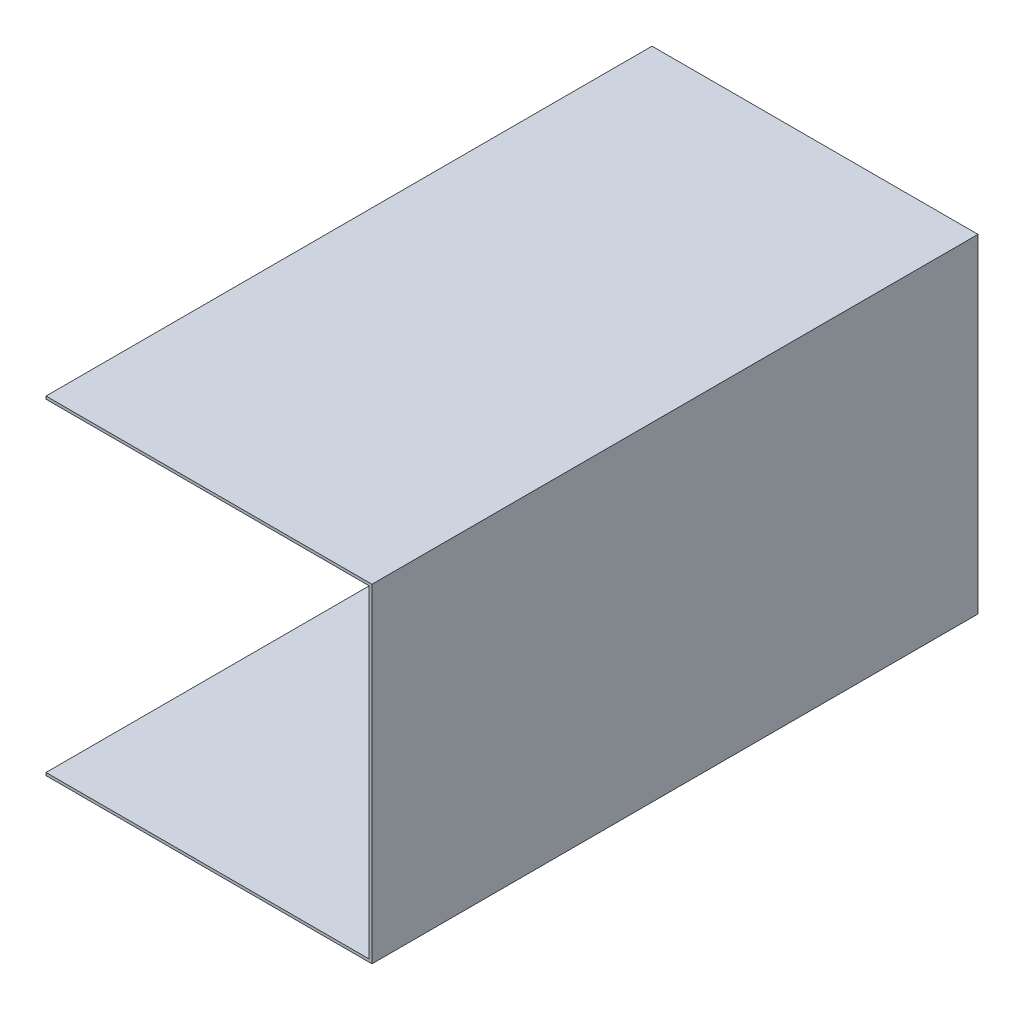
SolidWorks part; units mm, degrees
material "Beech"
ref_plane "Front Plane" through (0, 0, 0) normal (0, 0, 1) x (1, 0, 0)
ref_plane "Top Plane" through (0, 0, 0) normal (0, 1, 0) x (1, 0, 0)
ref_plane "Right Plane" through (0, 0, 0) normal (1, 0, 0) x (0, 0, -1)
sketch "Sketch1" plane through (0, 0, 0) normal (0, 0, 1) x (1, 0, 0)
  line L0 (-320, -320) -> (-320, -325.5)
  line L1 (-320, -320) -> (320, -320)
  line L2 (-320, -320) -> (-320, 320)
  line L3 (-320, 320) -> (320, 320)
  line L4 (320, -320) -> (320, 320)
  line L5 (-320, -320) -> (320, 320) construction
  line L6 (-320, 320) -> (320, -320) construction
  line L7 (-320, -325.5) -> (325.5, -325.5)
  line L9 (-320, 325.5) -> (325.5, 325.5)
  line L10 (325.5, -325.5) -> (325.5, 325.5)
  line L11 (-320, -320) -> (325.5, 325.5) construction
  line L12 (-320, 320) -> (325.5, -325.5) construction
  line L13 (-320, 320) -> (-320, 325.5)
  point P0 (0, 0)
  point P6 (0, 0)
  dimension "D1" = 640
  dimension "D2" = 5.5
extrude "Boss-Extrude1" add sketch "Sketch1" along normal blind 1200 contours L13 L3 L4 L1 L0 L7 L10 L9
